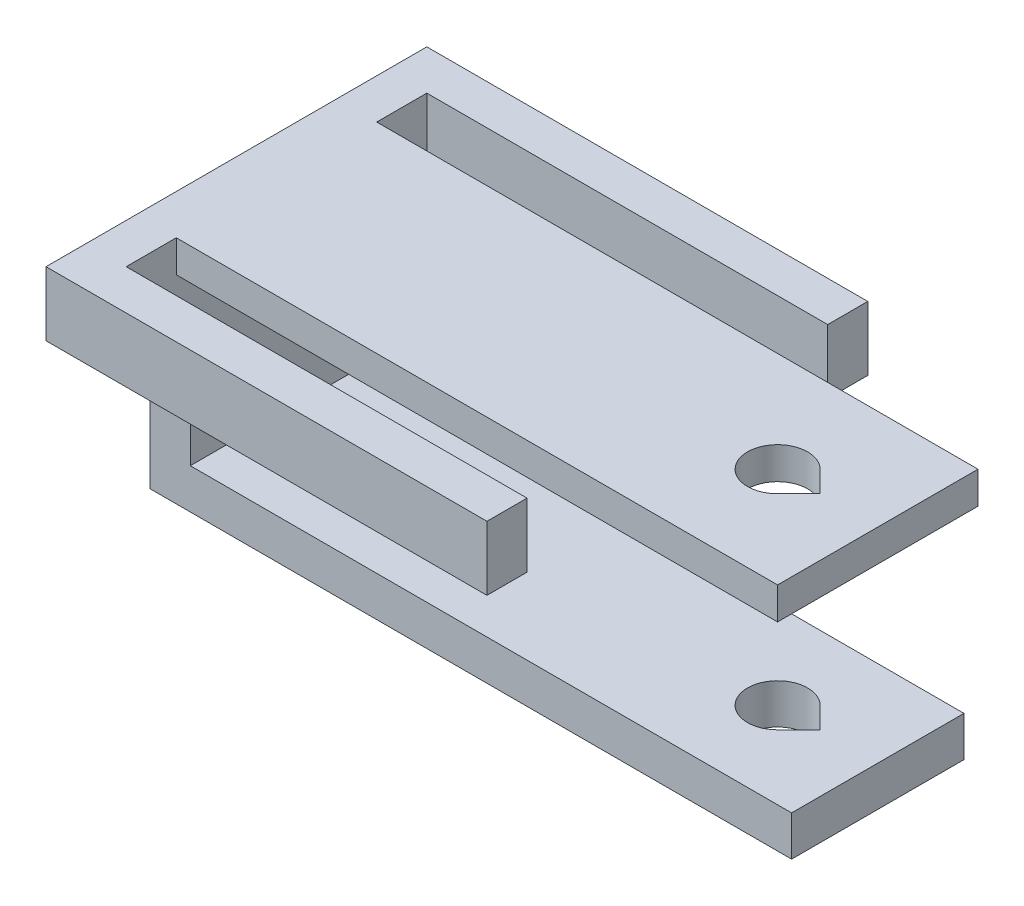
SolidWorks part; units mm, degrees
ref_plane "Спереди" through (0, 0, 0) normal (0, 0, 1) x (1, 0, 0)
ref_plane "Сверху" through (0, 0, 0) normal (0, 1, 0) x (1, 0, 0)
ref_plane "Справа" through (0, 0, 0) normal (1, 0, 0) x (0, 0, -1)
sketch "Эскиз1" plane through (0, 0, 0) normal (0, 1, 0) x (1, 0, 0)
  line L1 (0, 0) -> (20, 0)
  line L2 (0, 0) -> (0, 10)
  line L3 (0, 10) -> (20, 10)
  line L4 (20, 0) -> (20, 10)
  dimension "D1" = 10
  dimension "D2" = 20
extrude "Бобышка-Вытянуть1" add sketch "Эскиз1" along normal blind 1.6 contours L2 L3 L4 L1
sketch "Эскиз2" plane through (0, 0, 0) normal (-1, 0, 0) x (0, 0, 1)
  line L0 (0, 1.6) -> (-10, 1.6) construction
  line L1 (-14.5, 1.6) -> (4.5, 1.6)
  line L2 (-14.5, 1.6) -> (-14.5, -1.6)
  line L3 (-9.3, -10.6) -> (-0.7, -10.6)
  line L4 (4.5, 1.6) -> (4.5, -1.6)
  line L5 (-14.5, -1.6) -> (-9.3, -1.6)
  line L6 (-9.3, -1.6) -> (-9.3, -10.6)
  line L7 (-0.7, -10.6) -> (-0.7, -1.6)
  line L8 (-0.7, -1.6) -> (4.5, -1.6)
  line L9 (-10, 1.6) -> (-10, 0) construction
  line L10 (0, 1.6) -> (0, 0) construction
  dimension "D1" = 0
  dimension "D2" = 12.2
  dimension "D3" = 4.5
  dimension "D4" = 4.5
  dimension "D5" = 3.2
  dimension "D6" = 3.2
  dimension "D7" = 8.6
  dimension "D8" = 5.2
  dimension "D9" = 5.2
extrude "Бобышка-Вытянуть2" add sketch "Эскиз2" along normal blind 2
sketch "Эскиз3" plane through (0, 0, 0) normal (1, 0, 0) x (0, 0, -1)
  line L0 (0.7, -1.6) -> (-4.5, -1.6) construction
  line L1 (-4.5, 1.6) -> (-2.5, 1.6)
  line L2 (-4.5, 1.6) -> (-4.5, -1.6)
  line L3 (-4.5, -1.6) -> (-2.5, -1.6)
  line L4 (-2.5, 1.6) -> (-2.5, -1.6)
  line L5 (14.5, -1.6) -> (9.3, -1.6) construction
  line L6 (14.5, 1.6) -> (12.5, 1.6)
  line L7 (14.5, 1.6) -> (14.5, -1.6)
  line L8 (14.5, -1.6) -> (12.5, -1.6)
  line L9 (12.5, 1.6) -> (12.5, -1.6)
  line L10 (0, 1.6) -> (0, 0) construction
  line L11 (10, 1.6) -> (10, 0) construction
  line L12 (9.3, -1.6) -> (9.3, -10.6) construction
  line L13 (0.7, -10.6) -> (9.3, -10.6)
  line L14 (0.7, -10.6) -> (0.7, -8.6)
  line L15 (0.7, -8.6) -> (9.3, -8.6)
  line L16 (9.3, -10.6) -> (9.3, -8.6)
  dimension "D1" = 2.5
  dimension "D2" = 2.5
  dimension "D3" = 2
extrude "Бобышка-Вытянуть3" add sketch "Эскиз3" along normal blind 20
sketch "Эскиз4" plane through (20, 0, 0) normal (1, 0, 0) x (0, 0, -1)
  line L1 (0.7, -8.6) -> (9.3, -8.6)
  line L2 (0.7, -8.6) -> (0.7, -10.6)
  line L3 (0.7, -10.6) -> (9.3, -10.6)
  line L4 (9.3, -8.6) -> (9.3, -10.6)
  line L5 (10, 1.6) -> (0, 1.6)
  line L6 (10, 1.6) -> (10, 0)
  line L7 (10, 0) -> (0, 0)
  line L8 (0, 1.6) -> (0, 0)
extrude "Бобышка-Вытянуть4" add sketch "Эскиз4" along normal blind 10
sketch "Эскиз5" plane through (0, -10.6, 0) normal (0, -1, 0) x (1, 0, 0)
  line L0 (-2, -0.7) -> (30, -0.7) construction
  line L1 (-2, -9.3) -> (30, -9.3) construction
  line L2 (30, -0.7) -> (30, -9.3) construction
  line L3 (25, -3.5) -> (25, -6.5) construction
  line L4 (26.0607, -6.0607) -> (27.1213, -5)
  line L5 (27.1213, -5) -> (26.0607, -3.9393)
  arc A0 (26.0607, -3.9393) -> (26.0607, -6.0607) centre (25, -5) ccw
  point P10 (23.025, -2.0306)
  dimension "D1" = 3
  dimension "D2" = 4.3
  dimension "D3" = 4.3
  dimension "D4" = 5
  dimension "D5" = 45
  dimension "D6" = 45
extrude "Вырез-Вытянуть3" cut sketch "Эскиз5" against normal blind 15
